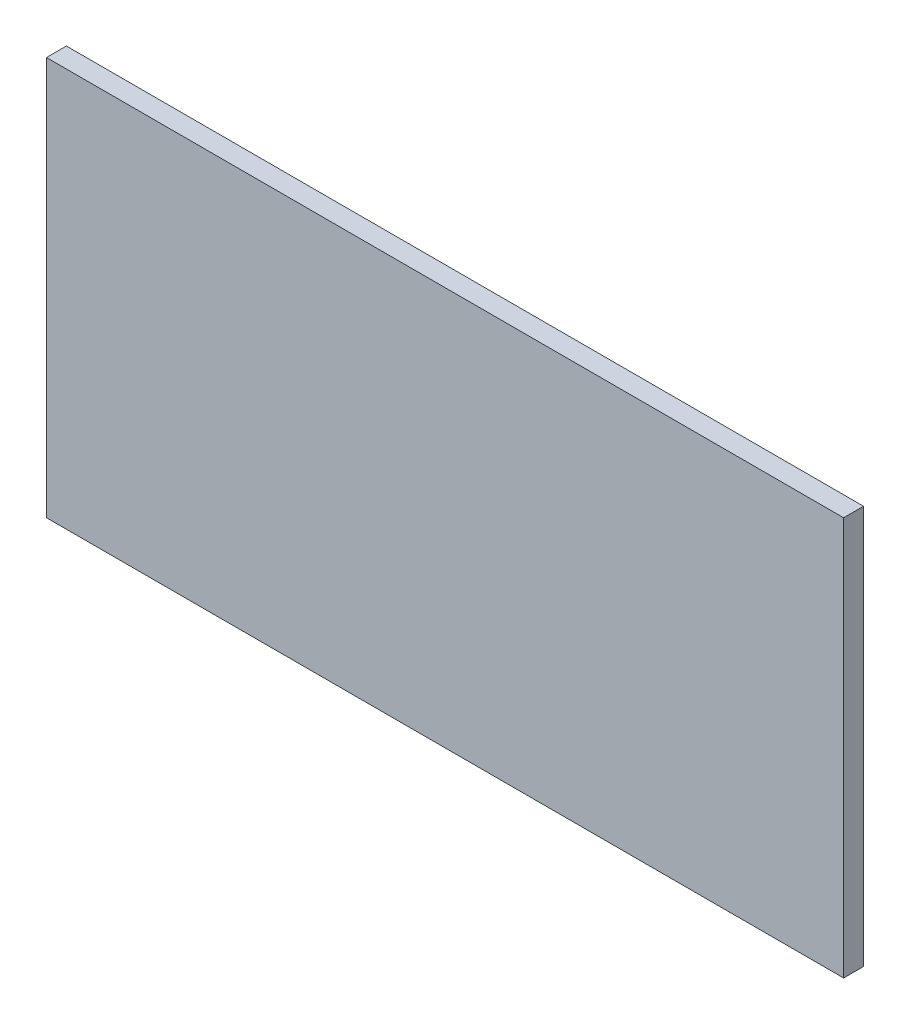
SolidWorks part; units mm, degrees
material "Pin"
ref_plane "Front" through (0, 0, 0) normal (0, 0, 1) x (1, 0, 0)
ref_plane "Top" through (0, 0, 0) normal (0, 1, 0) x (1, 0, 0)
ref_plane "Right" through (0, 0, 0) normal (1, 0, 0) x (0, 0, -1)
sketch "Esquisse1" plane through (0, 0, 0) normal (0, 0, 1) x (1, 0, 0)
  line L1 (-63.5, 31.75) -> (63.5, 31.75)
  line L2 (-63.5, 31.75) -> (-63.5, -31.75)
  line L3 (-63.5, -31.75) -> (63.5, -31.75)
  line L4 (63.5, 31.75) -> (63.5, -31.75)
  line L5 (-63.5, 31.75) -> (63.5, -31.75) construction
  line L6 (-63.5, -31.75) -> (63.5, 31.75) construction
  point P0 (0, 0)
  dimension "D1" = 63.5
  dimension "D2" = 127
extrude "Boss.-Extru.1" add sketch "Esquisse1" along normal blind 3.175
